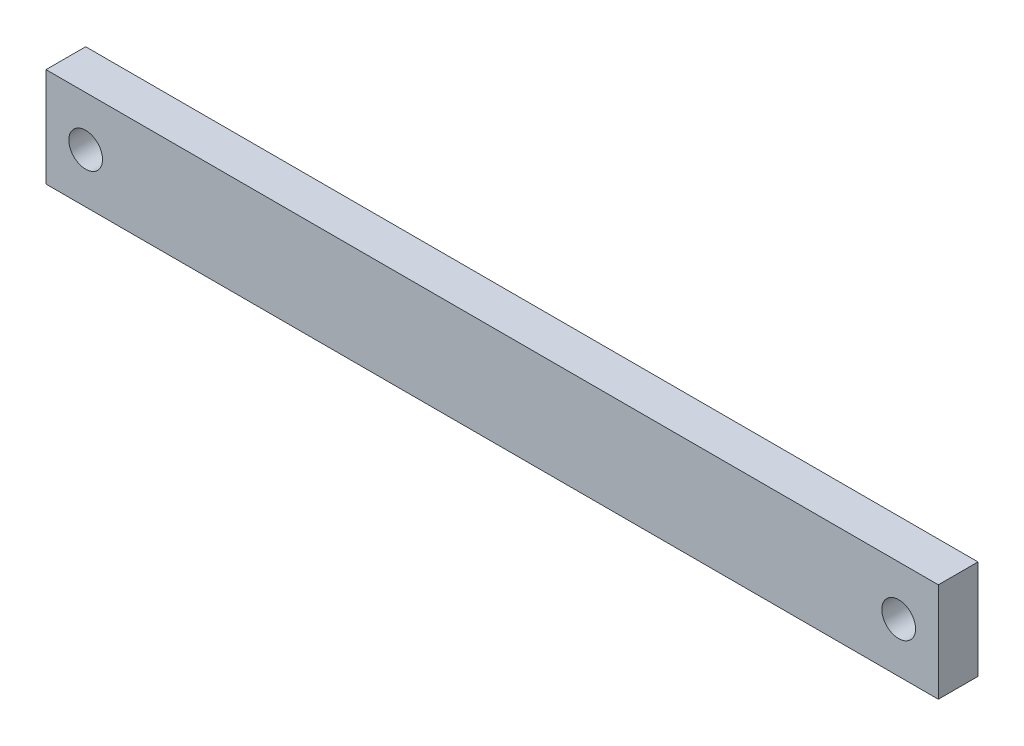
SolidWorks part; units mm, degrees
ref_plane "前视基准面" through (0, 0, 0) normal (0, 0, 1) x (1, 0, 0)
ref_plane "上视基准面" through (0, 0, 0) normal (0, 1, 0) x (1, 0, 0)
ref_plane "右视基准面" through (0, 0, 0) normal (1, 0, 0) x (0, 0, -1)
other "Configuration Table"
sketch "草图1" plane through (0, 0, 0) normal (0, 0, 1) x (1, 0, 0)
  line L1 (-39, -5) -> (51, -5)
  line L2 (-39, -5) -> (-39, 5)
  line L3 (-39, 5) -> (51, 5)
  line L4 (51, -5) -> (51, 5)
extrude "Battery_removable_clamp_bar" add sketch "草图1" along normal blind 4 from offset 43
sketch "草图2" plane through (0, 0, 0) normal (0, 0, 1) x (1, 0, 0)
  circle A0 centre (-35, 0) radius 1.7
  circle A1 centre (47, 0) radius 1.7
extrude "Clamp_two_M3" cut sketch "草图2" against normal blind 6 from offset 48
